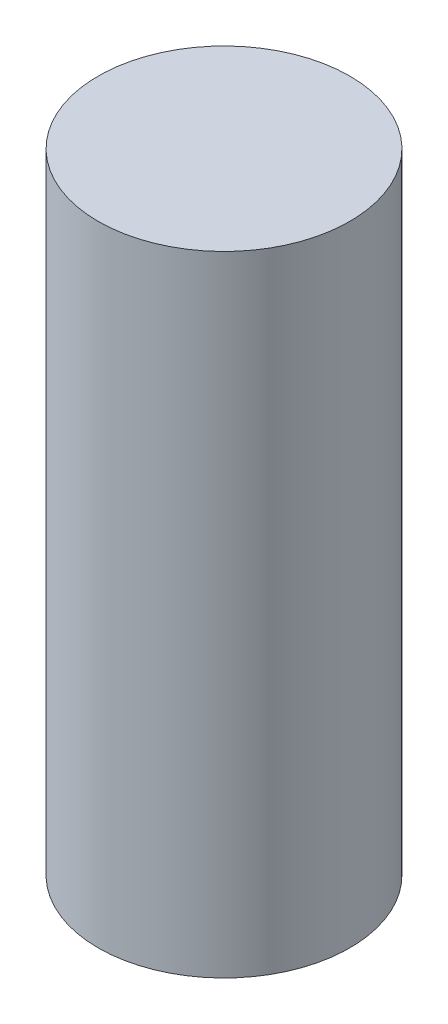
SolidWorks part; units mm, degrees
ref_plane "Front Plane" through (0, 0, 0) normal (0, 0, 1) x (1, 0, 0)
ref_plane "Top Plane" through (0, 0, 0) normal (0, 1, 0) x (1, 0, 0)
ref_plane "Right Plane" through (0, 0, 0) normal (1, 0, 0) x (0, 0, -1)
sketch "Sketch1" plane through (0, 0, 0) normal (0, 0, 1) x (1, 0, 0)
  line L1 (0, 0) -> (200, 0)
  line L2 (0, 0) -> (0, 1000)
  line L3 (0, 1000) -> (200, 1000)
  line L4 (200, 0) -> (200, 1000)
  point P5 (0, 0)
  point P7 (0, 0)
  point P8 (0, 0)
  point P9 (0, 0)
  point P10 (0, 0)
  dimension "D1" = 200
  dimension "D2" = 1000
revolve "Revolve1" add sketch "Sketch1" angle 360 about L2
